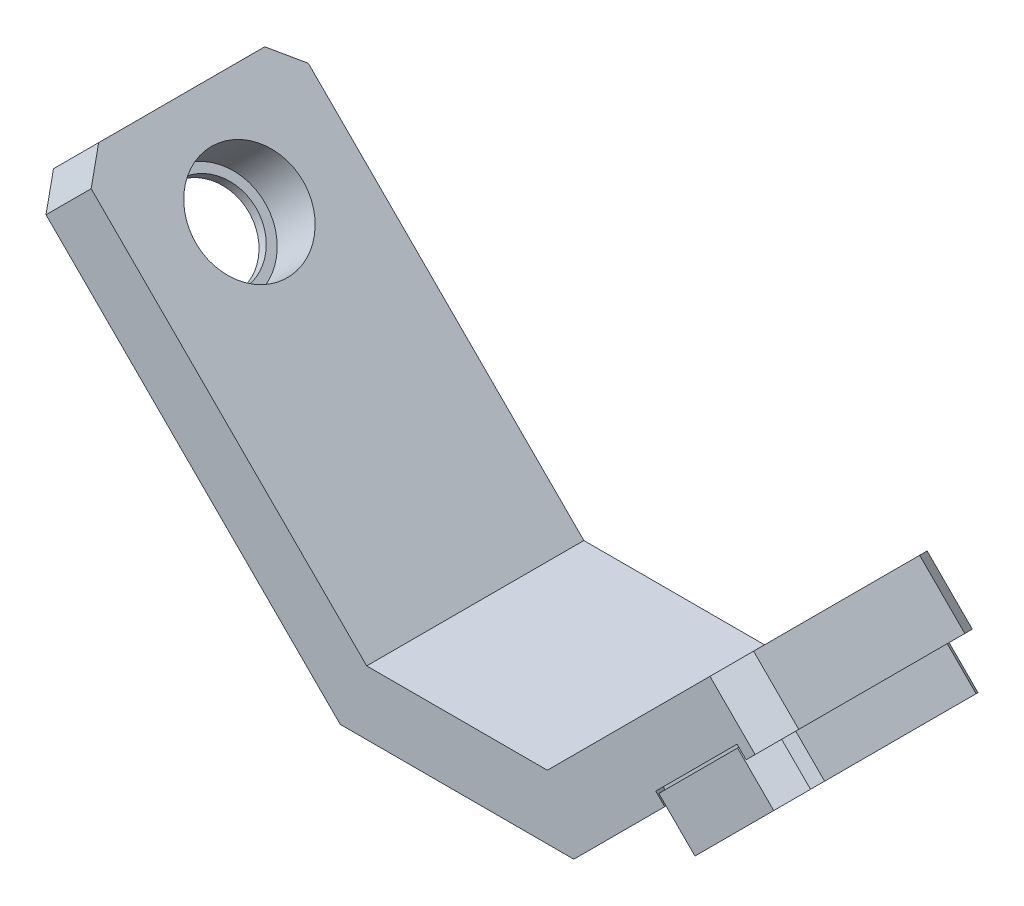
SolidWorks part; units mm, degrees
ref_plane "正面" through (0, 0, 0) normal (0, 0, 1) x (1, 0, 0)
ref_plane "平面" through (0, 0, 0) normal (0, 1, 0) x (1, 0, 0)
ref_plane "右側面" through (0, 0, 0) normal (1, 0, 0) x (0, 0, -1)
sketch "ｽｹｯﾁ1" plane through (0, 0, 0) normal (0, 0, 1) x (1, 0, 0)
  line L0 (0, 0) -> (-24.4454, 24.4454)
  line L1 (-24.4454, 24.4454) -> (-20.9099, 27.981)
  line L2 (-20.9099, 27.981) -> (2.0711, 5)
  line L3 (2.0711, 5) -> (16.2132, 5)
  line L4 (16.2132, 5) -> (30.3553, 19.1421)
  line L5 (30.3553, 19.1421) -> (33.8909, 15.6066)
  line L6 (33.8909, 15.6066) -> (18.2843, 0)
  line L7 (18.2843, 0) -> (0, 0)
  point P6 (23.2843, 12.0711)
  point P10 (-15.6066, 22.6777)
  dimension "D1" = 135
  dimension "D2" = 135
  dimension "D3" = 5
  dimension "D4" = 5
  dimension "D5" = 5
  dimension "D8" = 25
  dimension "D6" = 7.5
  dimension "D7" = 40
  dimension "D9" = 20
extrude "ﾎﾞｽ - 押し出し1" add sketch "ｽｹｯﾁ1" along normal mid plane 17
sketch "ｽｹｯﾁ2" plane through (0, 0, 0) normal (-0.7071, -0.7071, 0) x (0, 0, 1)
  line L1 (8.5, 34.5711) -> (-8.5, 34.5711) construction
  circle A0 centre (0, 27.0711) radius 4.2
  dimension "D1" = 8.4
  dimension "D2" = 7.5
extrude "ｶｯﾄ - 押し出し1" cut sketch "ｽｹｯﾁ2" along normal blind 4.2 from surface at -5 starting at face at (-9.4194, 16.4905, 0)
sketch "ｽｹｯﾁ3" plane through (9.1421, -9.1421, 0) normal (0.7071, -0.7071, 0) x (0, 0, -1)
  line L0 (-8.5, 35) -> (8.5, 35) construction
  line L1 (-6.5, 21) -> (6.5, 21)
  line L2 (6.5, 21) -> (6.5, 34)
  line L3 (6.5, 34) -> (-6.5, 34)
  line L4 (-6.5, 34) -> (-6.5, 21) construction
  line L5 (-6.5, 21) -> (-13, 27.5)
  line L6 (-13, 27.5) -> (-6.5, 34)
  circle A0 centre (0, 27.5) radius 6.5 construction
  point P7 (0, 35)
  dimension "D2" = 13
  dimension "D1" = 7.5
extrude "ｶｯﾄ - 押し出し2" cut sketch "ｽｹｯﾁ3" against normal blind 1
sketch "ｽｹｯﾁ5" plane through (8.435, -8.435, 0) normal (0.7071, -0.7071, 0) x (0, 0, -1)
  line L0 (-8.5, 35) -> (8.5, 35) construction
  circle A0 centre (0, 27.5) radius 1.9
  point P5 (0, 35)
  dimension "D2" = 3.8
  dimension "D1" = 7.5
extrude "ｶｯﾄ - 押し出し5" cut sketch "ｽｹｯﾁ5" against normal through all
chamfer "面取り1" distance 2 angle 45 4 edges at (32.1231, 17.3744, -8.5) (32.1231, 17.3744, 8.5) (-22.6777, 26.2132, 8.5) (-22.6777, 26.2132, -8.5)
sketch "ｽｹｯﾁ6" plane through (8.435, -8.435, 0) normal (0.7071, -0.7071, 0) x (0, 0, -1)
  line L4 (-8.5, 23.1414) -> (-8.5, 31.8586)
  line L5 (-8.5, 12.9289) -> (-8.5, 23) construction
  line L8 (-6.4586, 21.1) -> (6.4, 21.1)
  line L9 (6.4, 21.1) -> (6.4, 33.9)
  line L10 (6.4, 33.9) -> (-6.4586, 33.9)
  line L11 (-12.8586, 27.5) -> (-6.4586, 21.1)
  line L12 (-6.4586, 21.1) -> (6.4, 21.1)
  line L13 (6.4, 21.1) -> (6.4, 33.9)
  line L17 (-8.5, 23.1414) -> (-6.4586, 21.1)
  line L18 (-6.4586, 33.9) -> (-12.8586, 27.5)
  line L22 (6.4, 33.9) -> (-6.4586, 33.9)
  line L23 (-6.4586, 33.9) -> (-8.5, 31.8586)
  circle A0 centre (0, 27.5) radius 1.9 construction
  circle A1 centre (0, 27.5) radius 1.9
  dimension "D1" = 0.1
extrude "ﾎﾞｽ - 押し出し2" add sketch "ｽｹｯﾁ6" along normal blind 4 from offset 0.2 separate body
sketch "ｽｹｯﾁ7" plane through (11.4049, -11.4049, 0) normal (0.7071, -0.7071, 0) x (0, 0, -1)
  line L0 (-2.6375, 27.1375) -> (-3, 27.5) construction
  line L1 (-3, 27.5) -> (-2.6375, 27.8625) construction
  line L2 (0, 27.5) -> (-2.6375, 27.1375) construction
  line L3 (0, 27.5) -> (-2.6375, 27.8625) construction
  line L4 (0, 27.5) -> (-3, 27.5) construction
  line L5 (-2.6375, 27.1375) -> (-2.95, 27.45)
  line L6 (-2.95, 27.45) -> (-3.95, 27.45)
  line L7 (-2.95, 27.45) -> (-2.95, 27.55) construction
  line L8 (-2.95, 27.55) -> (-3.95, 27.55)
  line L9 (-3.95, 27.45) -> (-3.95, 27.55)
  line L10 (-2.95, 27.55) -> (-2.6375, 27.8625)
  line L11 (-2.6375, 27.8625) -> (-2.8541, 28.2478)
  line L12 (-2.8541, 28.2478) -> (-3.817, 28.5176)
  line L13 (-2.8271, 28.344) -> (-3.79, 28.6138)
  line L14 (-3.817, 28.5176) -> (-3.79, 28.6138)
  line L15 (-2.8271, 28.344) -> (-2.4419, 28.5607)
  line L16 (-2.4419, 28.5607) -> (-2.5465, 28.9901)
  line L17 (-2.5465, 28.9901) -> (-3.4009, 29.5096)
  line L18 (-2.4946, 29.0755) -> (-3.349, 29.5951)
  line L19 (-3.4009, 29.5096) -> (-3.349, 29.5951)
  line L20 (-2.4946, 29.0755) -> (-2.0652, 29.1801)
  line L21 (-2.0652, 29.1801) -> (-2.0501, 29.6218)
  line L22 (-2.0501, 29.6218) -> (-2.7326, 30.3527)
  line L23 (-1.977, 29.6901) -> (-2.6595, 30.4209)
  line L24 (-2.7326, 30.3527) -> (-2.6595, 30.4209)
  line L25 (-1.977, 29.6901) -> (-1.5353, 29.675)
  line L26 (-1.5353, 29.675) -> (-1.4016, 30.0963)
  line L27 (-1.4016, 30.0963) -> (-1.8617, 30.9841)
  line L28 (-1.3128, 30.1423) -> (-1.7729, 31.0301)
  line L29 (-1.8617, 30.9841) -> (-1.7729, 31.0301)
  line L30 (-1.3128, 30.1423) -> (-0.8915, 30.0086)
  line L31 (-0.8915, 30.0086) -> (-0.6491, 30.3781)
  line L32 (-0.6491, 30.3781) -> (-0.8526, 31.3572)
  line L33 (-0.5512, 30.3985) -> (-0.7547, 31.3776)
  line L34 (-0.8526, 31.3572) -> (-0.7547, 31.3776)
  line L35 (-0.5512, 30.3985) -> (-0.1817, 30.1561)
  line L36 (-0.1817, 30.1561) -> (0.1514, 30.4465)
  line L37 (0.1514, 30.4465) -> (0.2197, 31.4442)
  line L38 (0.2512, 30.4397) -> (0.3194, 31.4374)
  line L39 (0.2197, 31.4442) -> (0.3194, 31.4374)
  line L40 (0.2512, 30.4397) -> (0.5417, 30.1066)
  line L41 (0.5417, 30.1066) -> (0.9408, 30.2964)
  line L42 (0.9408, 30.2964) -> (1.2757, 31.2387)
  line L43 (1.035, 30.2629) -> (1.3699, 31.2052)
  line L44 (1.2757, 31.2387) -> (1.3699, 31.2052)
  line L45 (1.035, 30.2629) -> (1.2248, 29.8638)
  line L46 (1.2248, 29.8638) -> (1.6604, 29.9389)
  line L47 (1.6604, 29.9389) -> (2.237, 30.7559)
  line L48 (1.7421, 29.8812) -> (2.3187, 30.6982)
  line L49 (2.237, 30.7559) -> (2.3187, 30.6982)
  line L50 (1.7421, 29.8812) -> (1.8171, 29.4457)
  line L51 (1.8171, 29.4457) -> (2.2568, 29.4005)
  line L52 (2.2568, 29.4005) -> (3.0325, 30.0316)
  line L53 (2.3199, 29.3229) -> (3.0956, 29.954)
  line L54 (3.0325, 30.0316) -> (3.0956, 29.954)
  line L55 (2.3199, 29.3229) -> (2.2747, 28.8833)
  line L56 (2.2747, 28.8833) -> (2.6859, 28.7211)
  line L57 (2.6859, 28.7211) -> (3.6031, 29.1195)
  line L58 (2.7257, 28.6294) -> (3.6429, 29.0278)
  line L59 (3.6031, 29.1195) -> (3.6429, 29.0278)
  line L60 (2.7257, 28.6294) -> (2.5636, 28.2183)
  line L61 (2.5636, 28.2183) -> (2.9157, 27.9512)
  line L62 (2.9157, 27.9512) -> (3.9064, 28.0874)
  line L63 (2.9293, 27.8522) -> (3.92, 27.9883)
  line L64 (3.9064, 28.0874) -> (3.92, 27.9883)
  line L65 (2.9293, 27.8522) -> (2.6623, 27.5)
  line L66 (2.6623, 27.5) -> (2.9293, 27.1478)
  line L67 (2.9293, 27.1478) -> (3.92, 27.0117)
  line L68 (2.9157, 27.0488) -> (3.9064, 26.9126)
  line L69 (3.92, 27.0117) -> (3.9064, 26.9126)
  line L70 (2.9157, 27.0488) -> (2.5636, 26.7817)
  line L71 (2.5636, 26.7817) -> (2.7257, 26.3706)
  line L72 (2.7257, 26.3706) -> (3.6429, 25.9722)
  line L73 (2.6859, 26.2789) -> (3.6031, 25.8805)
  line L74 (3.6429, 25.9722) -> (3.6031, 25.8805)
  line L75 (2.6859, 26.2789) -> (2.2747, 26.1167)
  line L76 (2.2747, 26.1167) -> (2.3199, 25.6771)
  line L77 (2.3199, 25.6771) -> (3.0956, 25.046)
  line L78 (2.2568, 25.5995) -> (3.0325, 24.9684)
  line L79 (3.0956, 25.046) -> (3.0325, 24.9684)
  line L80 (2.2568, 25.5995) -> (1.8171, 25.5543)
  line L81 (1.8171, 25.5543) -> (1.7421, 25.1188)
  line L82 (1.7421, 25.1188) -> (2.3187, 24.3018)
  line L83 (1.6604, 25.0611) -> (2.237, 24.2441)
  line L84 (2.3187, 24.3018) -> (2.237, 24.2441)
  line L85 (1.6604, 25.0611) -> (1.2248, 25.1362)
  line L86 (1.2248, 25.1362) -> (1.035, 24.7371)
  line L87 (1.035, 24.7371) -> (1.3699, 23.7948)
  line L88 (0.9408, 24.7036) -> (1.2757, 23.7613)
  line L89 (1.3699, 23.7948) -> (1.2757, 23.7613)
  line L90 (0.9408, 24.7036) -> (0.5417, 24.8934)
  line L91 (0.5417, 24.8934) -> (0.2512, 24.5603)
  line L92 (0.2512, 24.5603) -> (0.3194, 23.5626)
  line L93 (0.1514, 24.5535) -> (0.2197, 23.5558)
  line L94 (0.3194, 23.5626) -> (0.2197, 23.5558)
  line L95 (0.1514, 24.5535) -> (-0.1817, 24.8439)
  line L96 (-0.1817, 24.8439) -> (-0.5512, 24.6015)
  line L97 (-0.5512, 24.6015) -> (-0.7547, 23.6224)
  line L98 (-0.6491, 24.6219) -> (-0.8526, 23.6428)
  line L99 (-0.7547, 23.6224) -> (-0.8526, 23.6428)
  line L100 (-0.6491, 24.6219) -> (-0.8915, 24.9914)
  line L101 (-0.8915, 24.9914) -> (-1.3128, 24.8577)
  line L102 (-1.3128, 24.8577) -> (-1.7729, 23.9699)
  line L103 (-1.4016, 24.9037) -> (-1.8617, 24.0159)
  line L104 (-1.7729, 23.9699) -> (-1.8617, 24.0159)
  line L105 (-1.4016, 24.9037) -> (-1.5353, 25.325)
  line L106 (-1.5353, 25.325) -> (-1.977, 25.3099)
  line L107 (-1.977, 25.3099) -> (-2.6595, 24.5791)
  line L108 (-2.0501, 25.3782) -> (-2.7326, 24.6473)
  line L109 (-2.6595, 24.5791) -> (-2.7326, 24.6473)
  line L110 (-2.0501, 25.3782) -> (-2.0652, 25.8199)
  line L111 (-2.0652, 25.8199) -> (-2.4946, 25.9245)
  line L112 (-2.4946, 25.9245) -> (-3.349, 25.4049)
  line L113 (-2.5465, 26.0099) -> (-3.4009, 25.4904)
  line L114 (-3.349, 25.4049) -> (-3.4009, 25.4904)
  line L115 (-2.5465, 26.0099) -> (-2.4419, 26.4393)
  line L116 (-2.4419, 26.4393) -> (-2.8271, 26.656)
  line L117 (-2.8271, 26.656) -> (-3.79, 26.3862)
  line L118 (-2.8541, 26.7522) -> (-3.817, 26.4824)
  line L119 (-3.79, 26.3862) -> (-3.817, 26.4824)
  line L120 (-2.8541, 26.7522) -> (-2.6375, 27.1375)
  circle A0 centre (0, 27.5) radius 3 construction
  circle A1 centre (0, 27.5) radius 2.6623 construction
  point P147 (0, 27.5)
  dimension "D1" = 6
  dimension "D2" = 7.826
  dimension "D3" = 7.826
  dimension "D4" = 0.1
  dimension "D5" = 1
  dimension "D6" = 23
extrude "ｶｯﾄ - 押し出し6" cut sketch "ｽｹｯﾁ7" against normal blind 3.4
sketch "ｽｹｯﾁ9" plane through (11.4049, -11.4049, 0) normal (0.7071, -0.7071, 0) x (0, 0, -1)
  line L1 (-8.5, 31.8586) -> (-8.5, 23.1414) construction
  circle A0 centre (4, 23.5) radius 1.4
  circle A1 centre (4, 31.5) radius 1.4
  circle A2 centre (-6, 27.5) radius 1.4
  circle A3 centre (0, 27.5) radius 1.9 construction
  point P13 (-8.5, 27.5)
  dimension "D1" = 2.8
  dimension "D2" = 4
  dimension "D6" = 6
  dimension "D3" = 4
  dimension "D4" = 4
  dimension "D5" = 4
extrude "ｶｯﾄ - 押し出し7" cut sketch "ｽｹｯﾁ9" against normal through all
sketch "ｽｹｯﾁ10" plane through (11.4049, -11.4049, 0) normal (0.7071, -0.7071, 0) x (0, 0, -1)
  line L1 (3.1, 23.5) -> (3.55, 22.7206)
  line L2 (3.55, 22.7206) -> (4.45, 22.7206)
  line L3 (4.45, 22.7206) -> (4.9, 23.5)
  line L4 (4.9, 23.5) -> (4.45, 24.2794)
  line L5 (4.45, 24.2794) -> (3.55, 24.2794)
  line L6 (3.55, 24.2794) -> (3.1, 23.5)
  line L7 (3.1, 31.5) -> (3.55, 30.7206)
  line L8 (3.55, 30.7206) -> (4.45, 30.7206)
  line L9 (4.45, 30.7206) -> (4.9, 31.5)
  line L10 (4.9, 31.5) -> (4.45, 32.2794)
  line L11 (4.45, 32.2794) -> (3.55, 32.2794)
  line L12 (3.55, 32.2794) -> (3.1, 31.5)
  line L13 (-6.9, 27.5) -> (-6.45, 26.7206)
  line L14 (-6.45, 26.7206) -> (-5.55, 26.7206)
  line L15 (-5.55, 26.7206) -> (-5.1, 27.5)
  line L16 (-5.1, 27.5) -> (-5.55, 28.2794)
  line L17 (-5.55, 28.2794) -> (-6.45, 28.2794)
  line L18 (-6.45, 28.2794) -> (-6.9, 27.5)
  circle A0 centre (4, 23.5) radius 0.7794 construction
  circle A1 centre (-6, 27.5) radius 1.4
  circle A2 centre (-6, 27.5) radius 1.4 construction
  circle A3 centre (4, 31.5) radius 1.4
  circle A4 centre (4, 31.5) radius 1.4 construction
  circle A5 centre (4, 23.5) radius 1.4
  circle A6 centre (4, 23.5) radius 1.4 construction
  circle A7 centre (4, 31.5) radius 0.7794 construction
  circle A8 centre (-6, 27.5) radius 0.7794 construction
  dimension "D4" = 1.8
  dimension "D1" = 0
  dimension "D2" = 0
  dimension "D3" = 0
extrude "ｶｯﾄ - 押し出し8" cut sketch "ｽｹｯﾁ10" against normal through all
chamfer "面取り3" distance 0.5 4 edges at (33.9616, 13.9803, -6.4) (24.9106, 4.9293, -6.4) (33.9616, 13.9803, 6.4586) (24.9106, 4.9293, 6.4586)
sketch "ｽｹｯﾁ11" plane through (0.5657, 0.5657, 0) normal (-0.7071, -0.7071, 0) x (0, 0, 1)
  circle A0 centre (0, 27.0711) radius 3.5
  dimension "D1" = 7
extrude "ｶｯﾄ - 押し出し9" cut sketch "ｽｹｯﾁ11" along normal blind 10
equation "\"D4@ｽｹｯﾁ1\"=\"D3@ｽｹｯﾁ1\""
equation "\"D5@ｽｹｯﾁ1\"=\"D3@ｽｹｯﾁ1\""
equation "\"D2@ｽｹｯﾁ7\"=360deg/46"
equation "\"D3@ｽｹｯﾁ7\"=\"D2@ｽｹｯﾁ7\""
